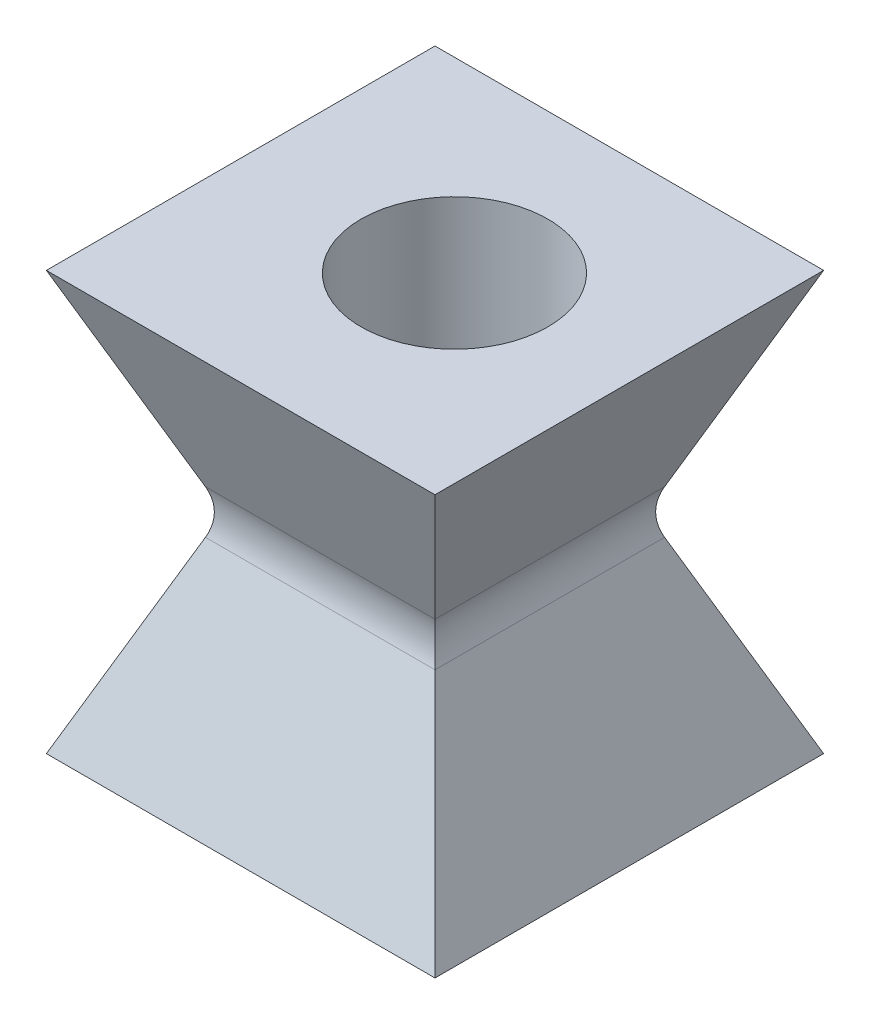
SolidWorks part; units mm, degrees
material "Acier inoxydable moulé"
ref_plane "Plan de face" through (0, 0, 0) normal (0, 0, 1) x (1, 0, 0)
ref_plane "Plan de dessus" through (0, 0, 0) normal (0, 1, 0) x (1, 0, 0)
ref_plane "Plan de droite" through (0, 0, 0) normal (1, 0, 0) x (0, 0, -1)
sketch "Esquisse1" plane through (0, 0, 0) normal (0, 0, 1) x (1, 0, 0)
  line L0 (0, 0) -> (56.4588, 0)
  line L1 (56.4588, 0) -> (80.2294, 56)
  line L2 (80.2294, 56) -> (-23.7706, 56)
  line L3 (-23.7706, 56) -> (0, 0)
  line L4 (56.4588, 0) -> (80.2294, -56)
  line L5 (80.2294, -56) -> (-23.7706, -56)
  line L6 (-23.7706, -56) -> (0, 0)
  dimension "D1" = 104
  dimension "D2" = 56
  dimension "D3" = 293
  dimension "D4" = 293
extrude "Boss.-Extru.1" add sketch "Esquisse1" along normal blind 104 contours L2 L3 L0 L1 | L6 L5 L4 L0
sketch "Esquisse3" plane through (0, 0, 0) normal (1, 0, 0) x (0, 0, -1)
  line L0 (0, -56) -> (-23.7706, 0)
  line L1 (-104, 0) -> (0, 0) construction
  line L2 (-104, -56) -> (-80.2294, 0)
  line L3 (0, -56) -> (0, 0) construction
  line L4 (-104, -56) -> (-104, 0) construction
  line L5 (-104, 56) -> (-80.2294, 0)
  line L6 (0, 56) -> (-23.7706, 0)
  line L7 (-23.7706, 0) -> (0, 0)
  line L8 (0, 0) -> (0, 56)
  line L9 (0, 0) -> (0, -56)
  line L10 (-80.2294, 0) -> (-104, 0)
  line L11 (-104, 0) -> (-104, 56)
  line L12 (-104, 0) -> (-104, -56)
  dimension "D1" = 23
  dimension "D2" = 23
extrude "Enlèv. mat.-Extru.1" cut sketch "Esquisse3" along normal through all both and the other way through all contours L7 L8 L6 | L9 L7 L0 | L11 L10 L5 | L10 L12 L2
sketch "Esquisse4" plane through (0, 56, 0) normal (0, 1, 0) x (1, 0, 0)
  line L0 (-23.7706, 0) -> (31.4375, 0)
  line L1 (80.2294, 0) -> (-23.7706, 0) construction
  line L2 (31.4375, 0) -> (31.4375, -50)
  circle A0 centre (31.4375, -50) radius 25
extrude "Enlèv. mat.-Extru.2" cut sketch "Esquisse4" against normal through all
fillet "Congé1" radius 15 4 edges at (0, 0, 52) (28.2294, 0, 23.7706) (56.4588, 0, 52) (28.2294, 0, 80.2294)
sketch "Esquisse5" plane through (0, 56, 0) normal (0, 1, 0) x (1, 0, 0)
equation "\"A\" = 112"
equation "\"B\" = 104"
equation "\"C\" = 23"
equation "\"D1@Esquisse1\"=\"B\""
equation "\"A/2\"= \"A\" / 2"
equation "\"D2@Esquisse1\"=\"A/2\""
equation "\"D3@Esquisse1\"=\"C\"+270"
equation "\"D4@Esquisse1\"=\"C\"+270"
equation "\"D1@Boss.-Extru.1\"=\"B\""
equation "\"D1@Esquisse3\"=\"C\""
equation "\"D2@Esquisse3\"=\"C\""
